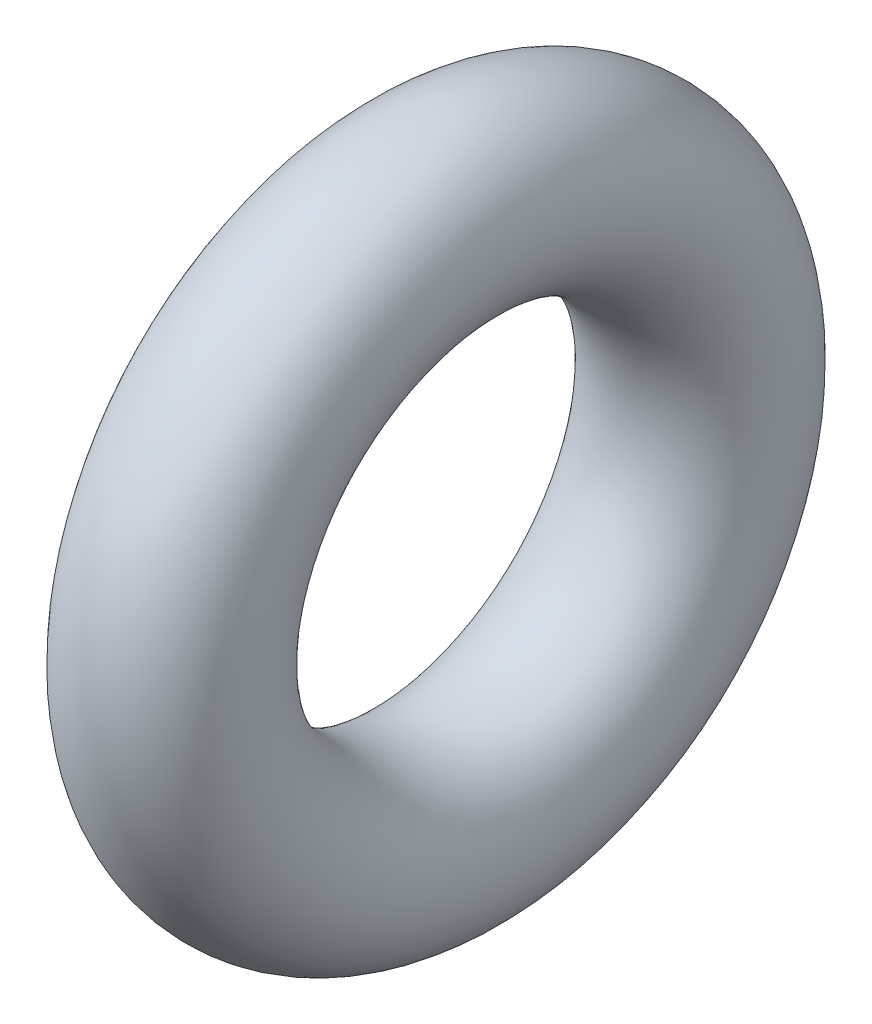
SolidWorks part; units mm, degrees
material "橡胶"
ref_plane "前视基准面" through (0, 0, 0) normal (0, 0, 1) x (1, 0, 0)
ref_plane "上视基准面" through (0, 0, 0) normal (0, 1, 0) x (1, 0, 0)
ref_plane "右视基准面" through (0, 0, 0) normal (1, 0, 0) x (0, 0, -1)
sketch "草图1" plane through (0, 0, 0) normal (0, 0, 1) x (1, 0, 0)
  line L0 (0, 0) -> (1.31, 0) construction
  line L1 (-0.9182, 5.8056) -> (0.9182, 5.8056) construction
  line L2 (-1.31, 5.82) -> (1.31, 5.82) construction
  line L3 (-1.31, 5.82) -> (-1.31, 3.2) construction
  line L4 (-1.31, 3.2) -> (1.31, 3.2) construction
  line L5 (1.31, 5.82) -> (1.31, 3.2) construction
  line L6 (-1.2956, 5.4282) -> (-1.2956, 3.5918) construction
  line L7 (-0.9182, 3.2144) -> (0.9182, 3.2144) construction
  line L8 (1.2956, 3.5918) -> (1.2956, 5.4282) construction
  line L9 (0, 0) -> (0, 3.2) construction
  line L10 (0, 0) -> (0, 3.93) construction
  arc A0 (-0.9182, 5.8056) -> (-1.2956, 5.4282) centre (-1.01, 5.52) ccw construction
  arc A1 (0.9182, 5.8056) -> (1.2956, 5.4282) centre (1.01, 5.52) cw construction
  arc A2 (-0.9182, 5.8056) -> (0.9182, 5.8056) centre (0, 8.6616) ccw construction
  arc A3 (-1.2956, 3.5918) -> (-0.9182, 3.2144) centre (-1.01, 3.5) ccw construction
  arc A4 (0.9182, 3.2144) -> (1.2956, 3.5918) centre (1.01, 3.5) ccw construction
  arc A5 (-1.2956, 5.4282) -> (-1.2956, 3.5918) centre (-4.1516, 4.51) cw construction
  arc A6 (1.2956, 5.4282) -> (1.2956, 3.5918) centre (4.1516, 4.51) ccw construction
  arc A7 (-0.9182, 3.2144) -> (0.9182, 3.2144) centre (0, 0.3584) cw construction
  circle A8 centre (0, 3.93) radius 1.315
  dimension "D3" = 0.3
  dimension "D4" = 0.3
  dimension "D5" = 3
  dimension "D7" = 2.63
  dimension "D1" = 2.62
  dimension "D2" = 3.2
  dimension "D6" = 3.93
revolve "旋转1" add sketch "草图1" angle 360 about L0
sketch "草图2" plane through (0, 0, 0) normal (1, 0, 0) x (0, 0, -1)
  circle A0 centre (0, 0) radius 2.25
  dimension "D1" = 4.5
